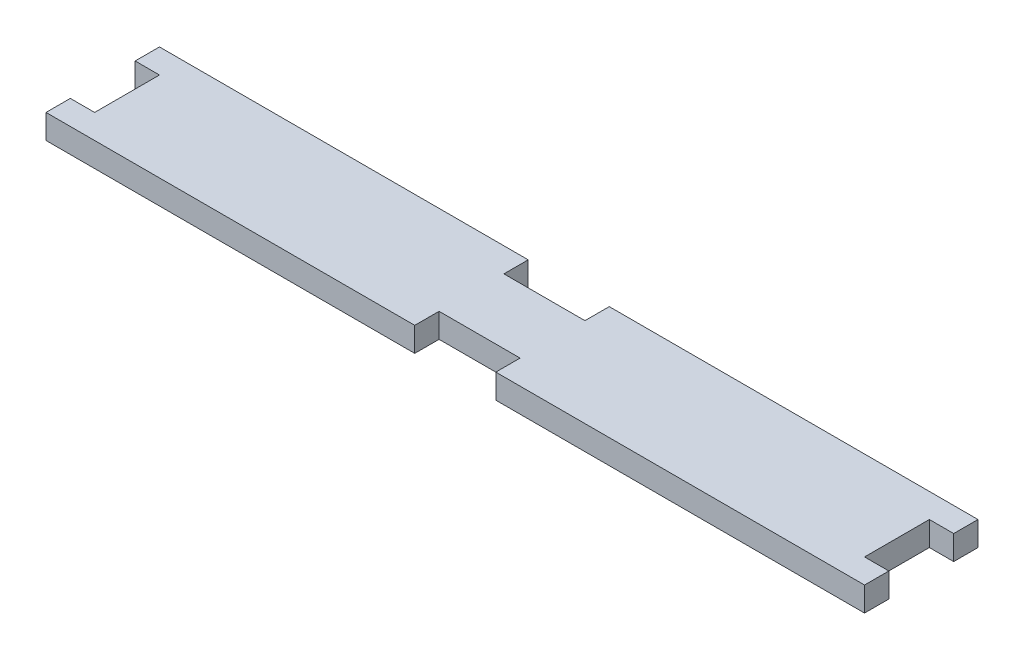
SolidWorks part; units mm, degrees
ref_plane "Plan de face" through (0, 0, 0) normal (0, 0, 1) x (1, 0, 0)
ref_plane "Plan de dessus" through (0, 0, 0) normal (0, 1, 0) x (1, 0, 0)
ref_plane "Plan de droite" through (0, 0, 0) normal (1, 0, 0) x (0, 0, -1)
sketch "Esquisse2" plane through (0, 22.2958, 0) normal (0, 1, 0) x (1, 0, 0)
  line L4 (-12.0031, -206) -> (-12.0031, -200)
  line L5 (-12.0031, -200) -> (-103.0031, -200)
  line L6 (-103.0031, -200) -> (-103.0031, -206)
  line L7 (-103.0031, -206) -> (-12.0031, -206)
  line L8 (-12.0031, -206) -> (-12.0031, -200)
  line L9 (-12.0031, -200) -> (-103.0031, -200)
  line L10 (-103.0031, -200) -> (-103.0031, -206)
  line L11 (-103.0031, -206) -> (-12.0031, -206)
  line L12 (98.9969, -200) -> (7.9969, -200)
  line L13 (7.9969, -200) -> (7.9969, -206)
  line L14 (7.9969, -206) -> (98.9969, -206)
  line L15 (98.9969, -206) -> (98.9969, -200)
  line L16 (98.9969, -200) -> (7.9969, -200)
  line L17 (7.9969, -200) -> (7.9969, -206)
  line L18 (7.9969, -206) -> (98.9969, -206)
  line L19 (98.9969, -206) -> (98.9969, -200)
  dimension "D1" = 0
  dimension "D2" = 0
extrude "Boss.-Extru.1" add sketch "Esquisse2" along normal blind 6
sketch "Esquisse3" plane through (0, 0, 200) normal (0, 0, -1) x (-1, 0, 0)
  line L2 (-7.9969, 28.2958) -> (12.0031, 28.2958)
  line L4 (-7.9969, 22.2958) -> (12.0031, 22.2958)
  line L8 (-98.9969, 22.2958) -> (-7.9969, 22.2958)
  line L9 (-7.9969, 22.2958) -> (-7.9969, 28.2958)
  line L10 (-7.9969, 28.2958) -> (-98.9969, 28.2958)
  line L11 (-98.9969, 28.2958) -> (-98.9969, 22.2958)
  line L12 (-98.9969, 22.2958) -> (-7.9969, 22.2958)
  line L14 (-7.9969, 28.2958) -> (-98.9969, 28.2958)
  line L15 (-98.9969, 28.2958) -> (-98.9969, 22.2958)
  line L16 (12.0031, 22.2958) -> (103.0031, 22.2958)
  line L17 (103.0031, 22.2958) -> (103.0031, 28.2958)
  line L18 (103.0031, 28.2958) -> (12.0031, 28.2958)
  line L19 (12.0031, 28.2958) -> (12.0031, 22.2958)
  line L20 (12.0031, 22.2958) -> (103.0031, 22.2958)
  line L21 (103.0031, 22.2958) -> (103.0031, 28.2958)
  line L22 (103.0031, 28.2958) -> (12.0031, 28.2958)
  dimension "D1" = 0
  dimension "D2" = 0
extrude "Boss.-Extru.2" add sketch "Esquisse3" along normal blind 22
sketch "Esquisse4" plane through (0, 28.2958, 0) normal (0, 1, 0) x (1, 0, 0)
  line L0 (-103.0031, -192) -> (98.9969, -192) construction
  line L1 (-103.0031, -178) -> (-103.0031, -206) construction
  line L2 (98.9969, -178) -> (98.9969, -206) construction
  line L3 (-2.0031, -178) -> (-2.0031, -211.4898) construction
  line L4 (-103.0031, -178) -> (98.9969, -178) construction
  line L5 (-12.0031, -206) -> (-12.0031, -200) construction
  line L6 (-12.0031, -200) -> (7.9969, -200) construction
  line L7 (7.9969, -200) -> (7.9969, -206) construction
  line L8 (7.9969, -206) -> (-12.0031, -206) construction
  line L9 (-12.0031, -206) -> (-12.0031, -200)
  line L10 (-12.0031, -200) -> (7.9969, -200)
  line L11 (7.9969, -200) -> (7.9969, -206)
  line L12 (7.9969, -206) -> (-12.0031, -206)
  line L13 (7.9969, -184) -> (7.9969, -178)
  line L14 (7.9969, -178) -> (-12.0031, -178)
  line L15 (-12.0031, -178) -> (-12.0031, -184)
  line L16 (-12.0031, -184) -> (7.9969, -184)
extrude "Enlèv. mat.-Extru.1" cut sketch "Esquisse4" against normal blind 6
sketch "Esquisse5" plane through (0, 28.2958, 0) normal (0, 1, 0) x (1, 0, 0)
  line L0 (-2.0031, -184) -> (-2.0031, -200) construction
  line L1 (-12.0031, -184) -> (7.9969, -184) construction
  line L2 (-12.0031, -200) -> (7.9969, -200) construction
  line L3 (-103.0031, -192) -> (98.9969, -192) construction
  line L4 (-103.0031, -178) -> (-103.0031, -206) construction
  line L5 (98.9969, -178) -> (98.9969, -206) construction
  line L6 (98.9969, -184) -> (98.9969, -200)
  line L7 (-103.0031, -184) -> (-97.0031, -184)
  line L8 (-103.0031, -184) -> (-103.0031, -200)
  line L9 (-103.0031, -200) -> (-97.0031, -200)
  line L10 (-97.0031, -184) -> (-97.0031, -200)
  line L11 (98.9969, -200) -> (92.9969, -200)
  line L12 (92.9969, -184) -> (92.9969, -200)
  line L13 (98.9969, -184) -> (92.9969, -184)
  line L14 (-103.0031, -178) -> (-12.0031, -178) construction
  line L17 (-103.0031, -206) -> (-12.0031, -206) construction
  dimension "D1" = 6
  dimension "D2" = 6
  dimension "D3" = 6
extrude "Enlèv. mat.-Extru.2" cut sketch "Esquisse5" against normal blind 6
ref_plane "Plan1" through (-103.0031, 28.2958, 200) normal (1, 0, 0) x (0, 0, -1)
